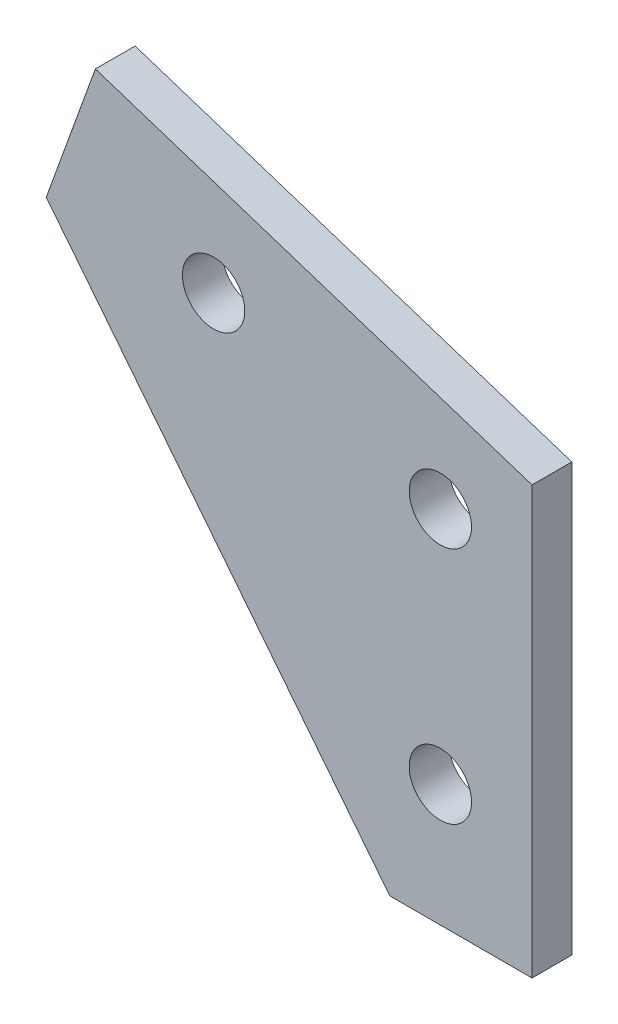
SolidWorks part; units mm, degrees
material "6061 Alloy"
ref_plane "Front Plane" through (0, 0, 0) normal (0, 0, 1) x (1, 0, 0)
ref_plane "Top Plane" through (0, 0, 0) normal (0, 1, 0) x (1, 0, 0)
ref_plane "Right Plane" through (0, 0, 0) normal (1, 0, 0) x (0, 0, -1)
sketch "Sketch4" plane through (0, 0, 0) normal (0, 0, 1) x (1, 0, 0)
  line L0 (-40.9906, 297.6036) -> (-42.1877, 293.9197) construction
  line L1 (-40.9906, 297.6036) -> (-52.5693, 261.9727) construction
  line L2 (-42.1877, 293.9197) -> (-7.297, 282.5815)
  line L3 (-42.1877, 293.9197) -> (-46.1134, 283.0783)
  line L4 (-7.297, 282.5815) -> (-7.297, 248.4582)
  line L5 (-7.297, 248.4582) -> (-18.6537, 248.4582)
  line L6 (-18.6537, 248.4582) -> (-46.1134, 283.0783)
  dimension "D1" = 3.8735
extrude "Boss-Extrude1" add sketch "Sketch4" along normal blind 3.175
hole_wizard "#10 Clearance Hole1" positions "Sketch5" profile "Sketch6" hole size "#10" standard "ANSI Inch" end condition through all
sketch "Sketch5" plane through (0, 0, 3.175) normal (0, 0, 1) x (1, 0, 0)
  point P0 (-32.7403, 283.1387)
  point P3 (-14.6226, 277.2519)
  point P6 (-14.6226, 258.2019)
sketch "Sketch6" plane through (-32.7403, 283.1387, 3.175) normal (1, 0, 0) x (0, -1, 0)
  line L0 (0, 0) -> (0, 3.175)
  line L1 (0, 3.175) -> (2.4892, 3.175)
  line L2 (2.4892, 3.175) -> (2.4892, 0)
  line L5 (2.4892, 0) -> (0, 0)
  line L11 (0, -6.35) -> (0, 107.95) construction
  dimension "Thru Hole Dia." = 4.9784
  dimension "Thru Hole Depth" = 3.175
